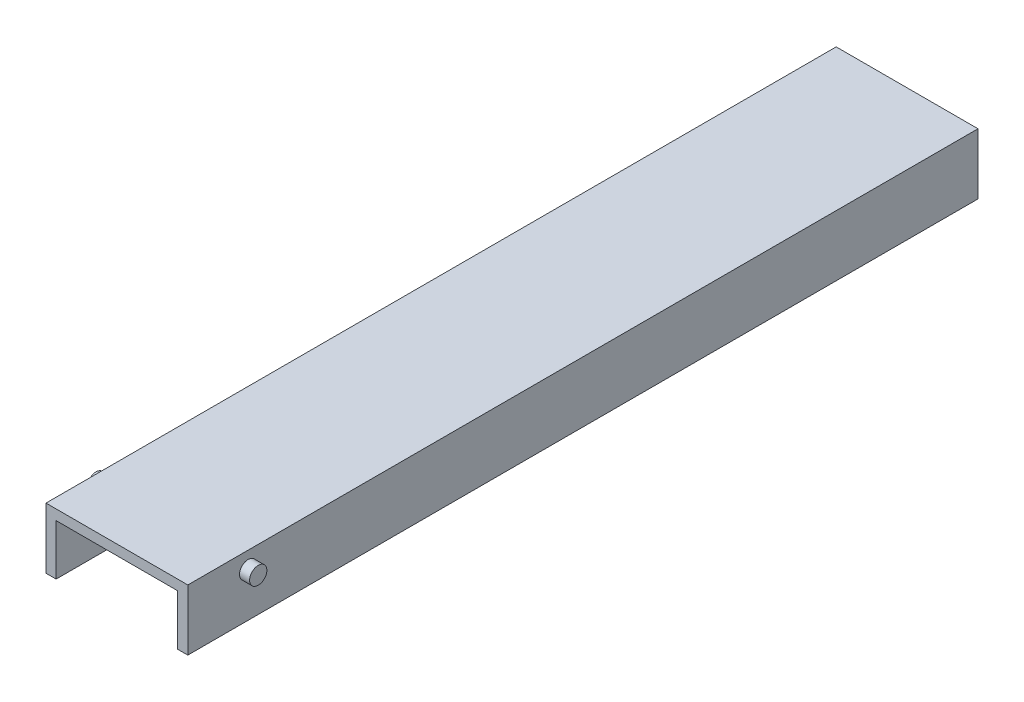
SolidWorks part; units mm, degrees
ref_plane "Front Plane" through (0, 0, 0) normal (0, 0, 1) x (1, 0, 0)
ref_plane "Top Plane" through (0, 0, 0) normal (0, 1, 0) x (1, 0, 0)
ref_plane "Right Plane" through (0, 0, 0) normal (1, 0, 0) x (0, 0, -1)
sketch "Sketch1" plane through (0, 0, 0) normal (0, 1, 0) x (1, 0, 0)
  line L1 (-17.5, -97.5) -> (17.5, -97.5)
  line L2 (-17.5, -97.5) -> (-17.5, 97.5)
  line L3 (-17.5, 97.5) -> (17.5, 97.5)
  line L4 (17.5, -97.5) -> (17.5, 97.5)
  line L5 (-17.5, -97.5) -> (17.5, 97.5) construction
  line L6 (-17.5, 97.5) -> (17.5, -97.5) construction
  point P0 (0, 0)
extrude "Boss-Extrude1" add sketch "Sketch1" along normal blind 15
sketch "Sketch2" plane through (-17.5, 0, 0) normal (-1, 0, 0) x (0, 0, 1)
  line L3 (93.25, 13) -> (4.25, 13)
  line L5 (93.25, 8.75) -> (4.25, 8.75)
  arc A1 (4.25, 13) -> (4.25, 8.75) centre (4.25, 10.875) ccw
  arc A4 (93.25, 8.75) -> (93.25, 13) centre (93.25, 10.875) ccw
  circle A5 centre (93.25, 10.875) radius 2.125
extrude "Boss-Extrude2" add sketch "Sketch2" along normal blind 2.5 contours A4 A5
sketch "Sketch3" plane through (17.5, 0, 0) normal (1, 0, 0) x (0, 0, -1)
  circle A0 centre (-93.25, 10.875) radius 2.125
extrude "Boss-Extrude3" add sketch "Sketch3" along normal blind 2.5
sketch "Sketch4" plane through (0, 0, 97.5) normal (0, 0, 1) x (1, 0, 0)
  line L1 (-15, -12.5) -> (15, -12.5)
  line L2 (-15, -12.5) -> (-15, 12.5)
  line L3 (-15, 12.5) -> (15, 12.5)
  line L4 (15, -12.5) -> (15, 12.5)
  line L5 (-15, -12.5) -> (15, 12.5) construction
  line L6 (-15, 12.5) -> (15, -12.5) construction
  point P0 (0, 0)
extrude "Cut-Extrude1" cut sketch "Sketch4" against normal blind 260.5
sketch "Sketch5" plane through (-17.5, 0, 0) normal (-1, 0, 0) x (0, 0, 1)
  line L0 (-97.5, 0) -> (97.5, 0) construction
  line L1 (-97.5, 15) -> (-86.875, 15)
  line L2 (-97.5, 15) -> (-97.5, 0)
  line L3 (-97.5, 0) -> (-86.875, 0)
  line L4 (-86.875, 15) -> (-86.875, 0)
extrude "Cut-Extrude2" cut sketch "Sketch5" against normal blind 65
sketch "Sketch6" plane through (0, 0, 97.5) normal (0, 0, 1) x (1, 0, 0)
  line L0 (-17.5, 15) -> (17.5, 15)
  line L1 (17.5, 15) -> (17.5, 0)
  line L2 (17.5, 0) -> (15, 0)
  line L3 (15, 0) -> (15, 12.5)
  line L4 (15, 12.5) -> (-15, 12.5)
  line L5 (-15, 12.5) -> (-15, 0)
  line L6 (-15, 0) -> (-17.5, 0)
  line L7 (-17.5, 0) -> (-17.5, 15)
extrude "Boss-Extrude4" add sketch "Sketch6" along normal blind 10.625
